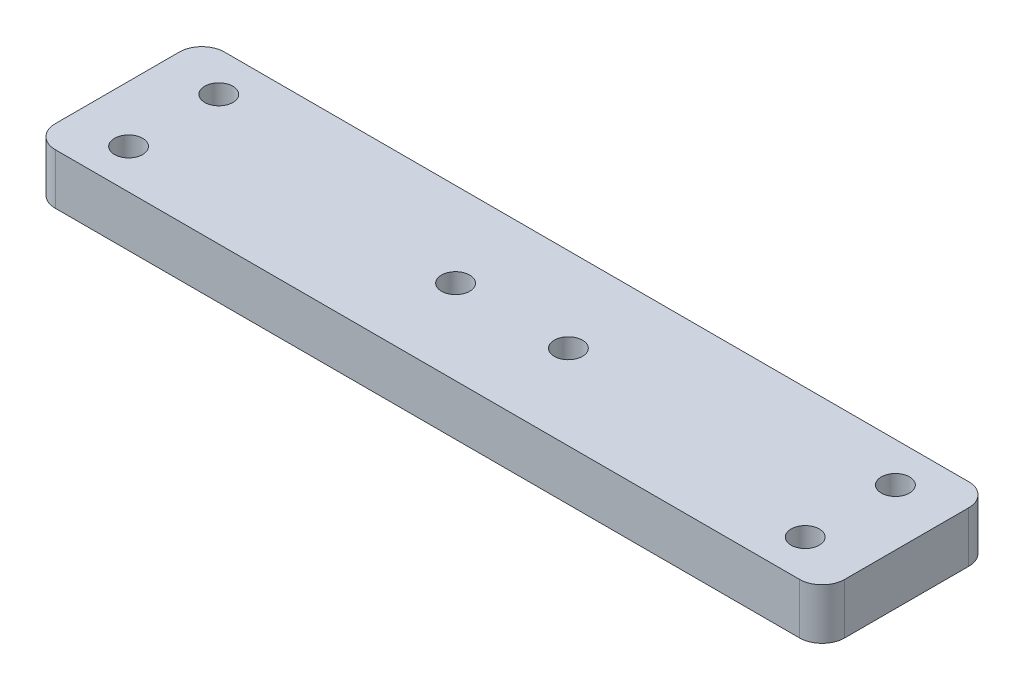
SolidWorks part; units mm, degrees
ref_plane "前视基准面" through (0, 0, 0) normal (0, 0, 1) x (1, 0, 0)
ref_plane "上视基准面" through (0, 0, 0) normal (0, 1, 0) x (1, 0, 0)
ref_plane "右视基准面" through (0, 0, 0) normal (1, 0, 0) x (0, 0, -1)
sketch "草图1" plane through (0, 0, 0) normal (0, 1, 0) x (1, 0, 0)
  line L0 (-5, 0) -> (5, 0) construction
  line L1 (-33, 7.5) -> (33, 7.5)
  line L2 (-35, 5.5) -> (-35, -5.5)
  line L3 (-33, -7.5) -> (33, -7.5)
  line L4 (35, 5.5) -> (35, -5.5)
  line L5 (-35, 7.5) -> (35, -7.5) construction
  line L6 (-35, -7.5) -> (35, 7.5) construction
  line L7 (-30, 4) -> (-30, -4) construction
  line L8 (0, 0) -> (-30, 0) construction
  circle A0 centre (-5, 0) radius 1.25
  circle A1 centre (5, 0) radius 1.25
  circle A2 centre (-30, 4) radius 1.25
  circle A3 centre (-30, -4) radius 1.25
  circle A4 centre (30, -4) radius 1.25
  circle A5 centre (30, 4) radius 1.25
  arc A10 (35, 5.5) -> (33, 7.5) centre (33, 5.5) ccw
  arc A11 (35, -5.5) -> (33, -7.5) centre (33, -5.5) cw
  arc A12 (-35, -5.5) -> (-33, -7.5) centre (-33, -5.5) ccw
  arc A13 (-35, 5.5) -> (-33, 7.5) centre (-33, 5.5) cw
  point P0 (0, 0)
  dimension "D4" = 2.5
  dimension "D7" = 2.5
  dimension "D9" = 2
  dimension "D1" = 15
  dimension "D2" = 70
  dimension "D3" = 10
  dimension "D5" = 30
  dimension "D6" = 8
  dimension "D8" = 2
extrude "凸台-拉伸1" add sketch "草图1" along normal blind 4.5
